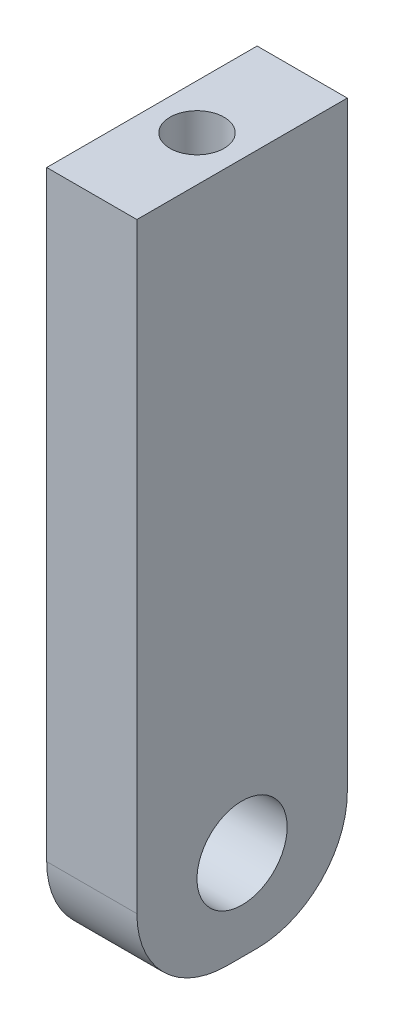
SolidWorks part; units mm, degrees
ref_plane "前视基准面" through (0, 0, 0) normal (0, 0, 1) x (1, 0, 0)
ref_plane "上视基准面" through (0, 0, 0) normal (0, 1, 0) x (1, 0, 0)
ref_plane "右视基准面" through (0, 0, 0) normal (1, 0, 0) x (0, 0, -1)
sketch "草图1" plane through (0, 0, 0) normal (0, 0, 1) x (1, 0, 0)
  line L6 (0, 0.5463) -> (0, -22.4537)
  line L7 (0, -22.4537) -> (3, -22.4537)
  line L8 (3, -22.4537) -> (3, 0.5463)
  line L9 (3, 0.5463) -> (0, 0.5463)
  dimension "D2" = 3
  dimension "24" = 23
extrude "凸台-拉伸1" add sketch "草图1" along normal blind 7
sketch "草图3" plane through (0, 0.5463, 0) normal (0, 1, 0) x (1, 0, 0)
  line L0 (0, -7) -> (0, 0) construction
  line L1 (3, 0) -> (0, 0) construction
  circle A0 centre (1.5, -3.5) radius 0.9
  point P6 (0, -3.5)
  point P7 (1.5, 0)
  dimension "D1" = 1.8
sketch "草图4" plane through (3, 0, 0) normal (1, 0, 0) x (0, 0, -1)
  line L0 (-7, -22.4537) -> (0, -22.4537) construction
  line L1 (-7, -22.4537) -> (-7, 0.5463) construction
  circle A0 centre (-3.5, -19.4537) radius 1.5
  dimension "D1" = 3
  dimension "D2" = 3
  dimension "D3" = 3.5
extrude "切除-拉伸2" cut sketch "草图4" against normal through all
fillet "圆角1" radius 3 2 edges at (1.5, -22.4537, 7) (1.5, -22.4537, 0)
extrude "切除-拉伸4" cut sketch "草图3" against normal blind 7
